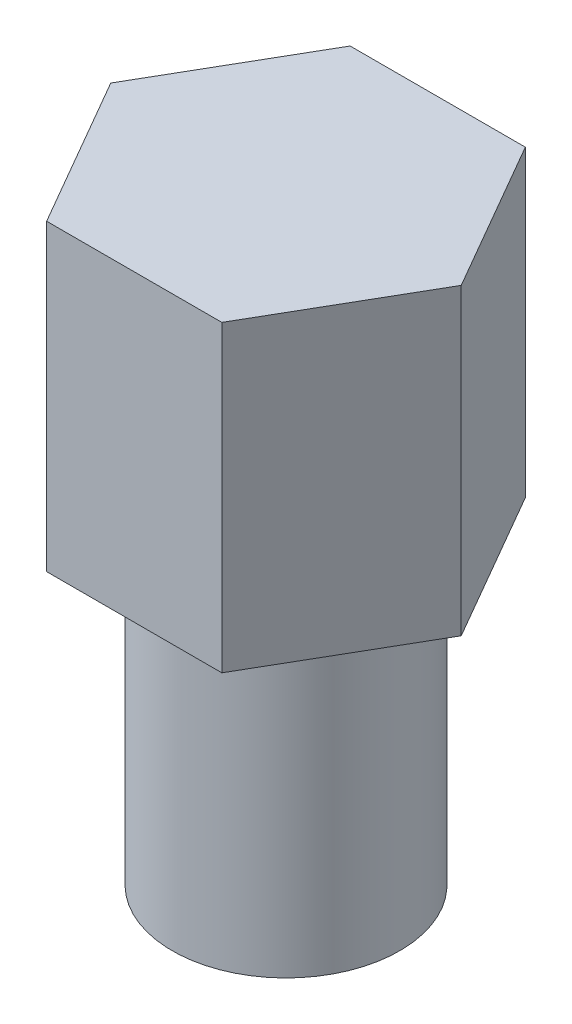
SolidWorks part; units mm, degrees
ref_plane "Front" through (0, 0, 0) normal (0, 0, 1) x (1, 0, 0)
ref_plane "Top" through (0, 0, 0) normal (0, 1, 0) x (1, 0, 0)
ref_plane "Right" through (0, 0, 0) normal (1, 0, 0) x (0, 0, -1)
sketch "Sketch1" plane through (0, 0, 0) normal (0, 1, 0) x (1, 0, 0)
  line L1 (3.6662, 6.35) -> (-3.6662, 6.35)
  line L2 (-3.6662, 6.35) -> (-7.3323, 0)
  line L3 (-7.3323, 0) -> (-3.6662, -6.35)
  line L4 (-3.6662, -6.35) -> (3.6662, -6.35)
  line L5 (3.6662, -6.35) -> (7.3323, 0)
  line L6 (7.3323, 0) -> (3.6662, 6.35)
  circle A0 centre (0, 0) radius 6.35 construction
  dimension "D1" = 12.7
extrude "Extrude1" add sketch "Sketch1" along normal blind 12.7
sketch "Sketch2" plane through (0, 0, 0) normal (0, -1, 0) x (1, 0, 0)
  circle A0 centre (0, 0) radius 4.7625
  dimension "D1" = 9.525
extrude "Extrude2" add sketch "Sketch2" along normal blind 12.7
cosmetic thread "Cosmetic Thread1" parameters "D1"=12.7, "D2"=7.1438
